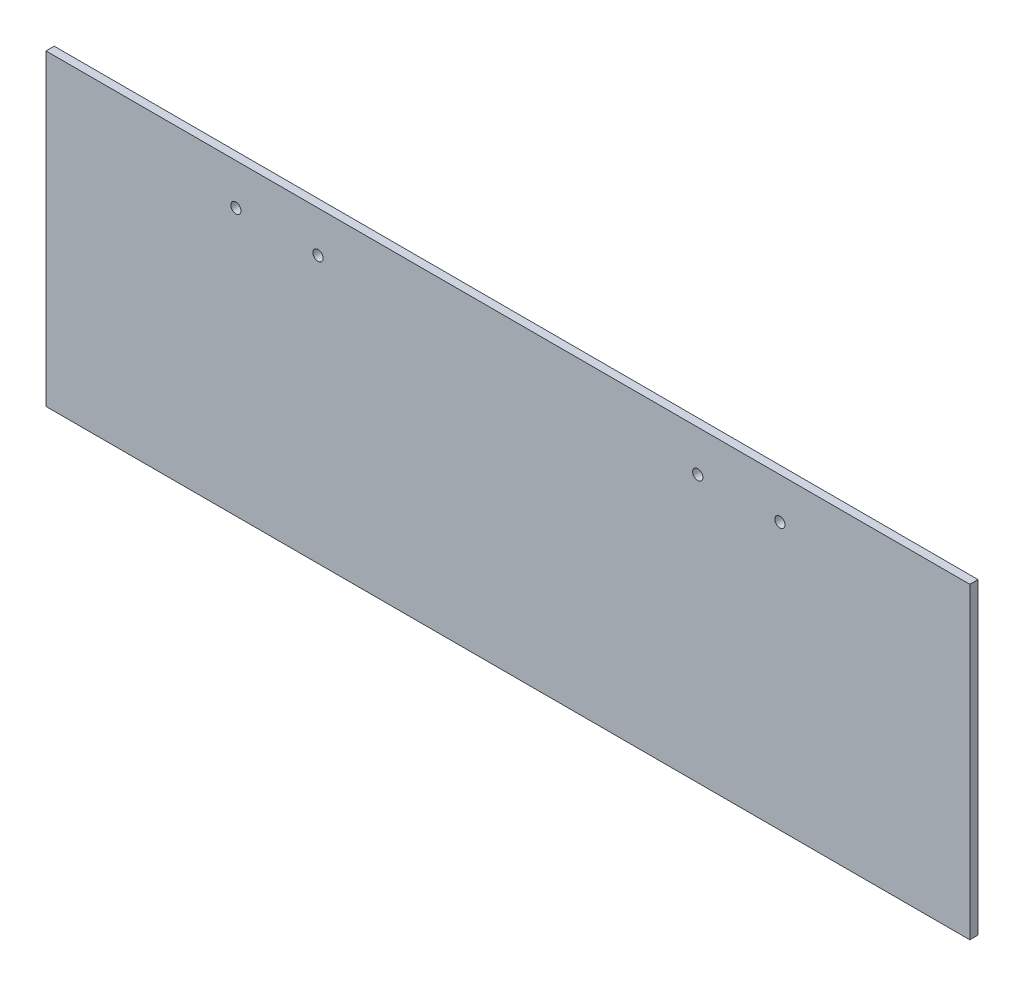
SolidWorks part; units mm, degrees
ref_plane "Front Plane" through (0, 0, 0) normal (0, 0, 1) x (1, 0, 0)
ref_plane "Top Plane" through (0, 0, 0) normal (0, 1, 0) x (1, 0, 0)
ref_plane "Right Plane" through (0, 0, 0) normal (1, 0, 0) x (0, 0, -1)
sketch "Sketch1" plane through (0, 0, 0) normal (0, 0, 1) x (1, 0, 0)
  line L0 (0, 192.9322) -> (0, -44.0869) construction
  line L1 (225, 150) -> (-225, 150)
  line L2 (225, 150) -> (225, 0)
  line L3 (225, 0) -> (-225, 0)
  line L4 (-225, 150) -> (-225, 0)
  line L5 (225, 150) -> (-225, 0) construction
  line L6 (225, 0) -> (-225, 150) construction
  line L7 (-199.2, 128.5) -> (175.2382, 128.5) construction
  point P0 (0, 75)
  point P5 (0, 0)
  point P11 (-132.5, 128.5)
  point P12 (-92.5, 128.5)
  point P13 (92.5, 128.5)
  point P14 (132.5, 128.5)
  dimension "D3" = 21.5
  dimension "D1" = 150
  dimension "D2" = 450
  dimension "D4" = 40
  dimension "D5" = 92.5
extrude "Boss-Extrude1" add sketch "Sketch1" along normal mid plane 4
sketch "Sketch2" plane through (0, 0, 2) normal (0, 0, 1) x (1, 0, 0)
  line L0 (-199.2, 130) -> (175.2382, 130) construction
  line L1 (0, 192.9322) -> (0, -44.0869) construction
  line L3 (225, 150) -> (-225, 150) construction
  line L4 (-225, 150) -> (-225, 0) construction
  point P23 (-132.5, 130)
  point P25 (-92.5, 130)
  point P30 (92.5, 130)
  point P31 (132.5, 130)
  dimension "D1" = 20
  dimension "D2" = 40
  dimension "D3" = 92.5
hole_wizard "Tap Drill for M6 Tap1" positions "Sketch2" profile "Sketch3" hole size "M6" standard "ISO" end condition through all
sketch "Sketch3" plane through (132.5, 130, 2) normal (1, 0, 0) x (0, -1, 0)
  line L0 (0, 0) -> (0, 4)
  line L1 (0, 4) -> (2.5, 4)
  line L2 (2.5, 4) -> (2.5, 0)
  line L5 (2.5, 0) -> (0, 0)
  line L11 (0, -6.35) -> (0, 107.95) construction
  dimension "Thru Hole Dia." = 5
  dimension "Thru Hole Depth" = 4
